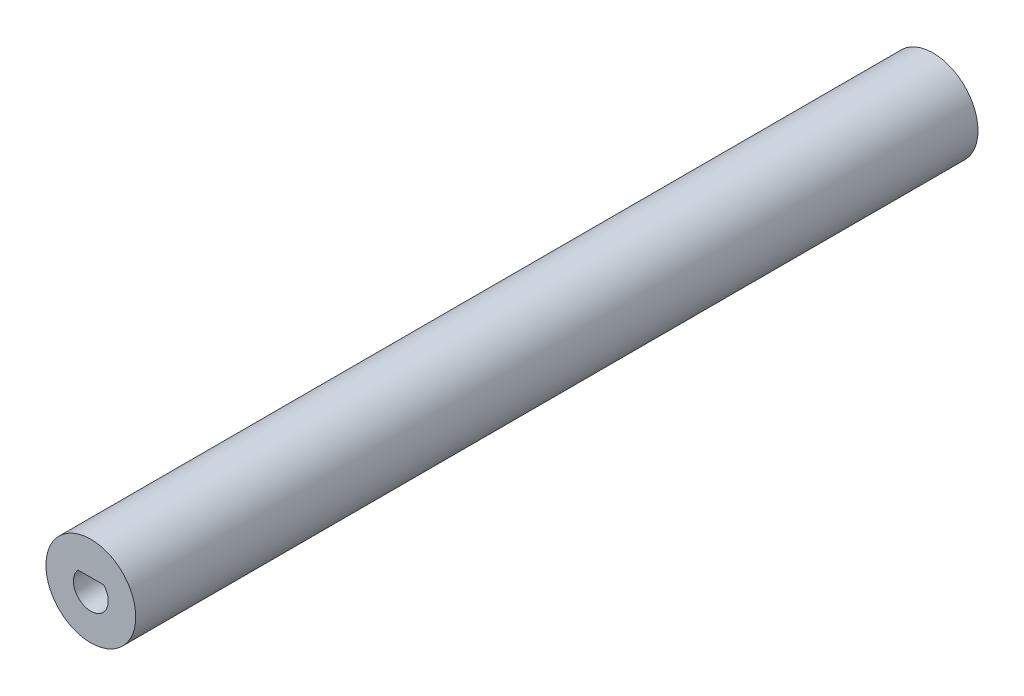
SolidWorks part; units mm, degrees
ref_plane "Ön Düzlem" through (0, 0, 0) normal (0, 0, 1) x (1, 0, 0)
ref_plane "Üst Düzlem" through (0, 0, 0) normal (0, 1, 0) x (1, 0, 0)
ref_plane "Sağ Düzlem" through (0, 0, 0) normal (1, 0, 0) x (0, 0, -1)
sketch "Çizim1" plane through (0, 0, 0) normal (0, 0, 1) x (1, 0, 0)
  circle A0 centre (0, 0) radius 4
  dimension "D1" = 8
extrude "Yükseklik-Ekstrüzyon1" add sketch "Çizim1" along normal blind 75
sketch "Çizim2" plane through (0, 0, 75) normal (0, 0, 1) x (1, 0, 0)
  line L0 (-1.1402, 1.05) -> (1.1402, 1.05)
  arc A0 (-1.1402, 1.05) -> (1.1402, 1.05) centre (0, 0) ccw
  dimension "D1" = 3.1
extrude "Kes-Ekstrüzyon1" cut sketch "Çizim2" against normal blind 7
